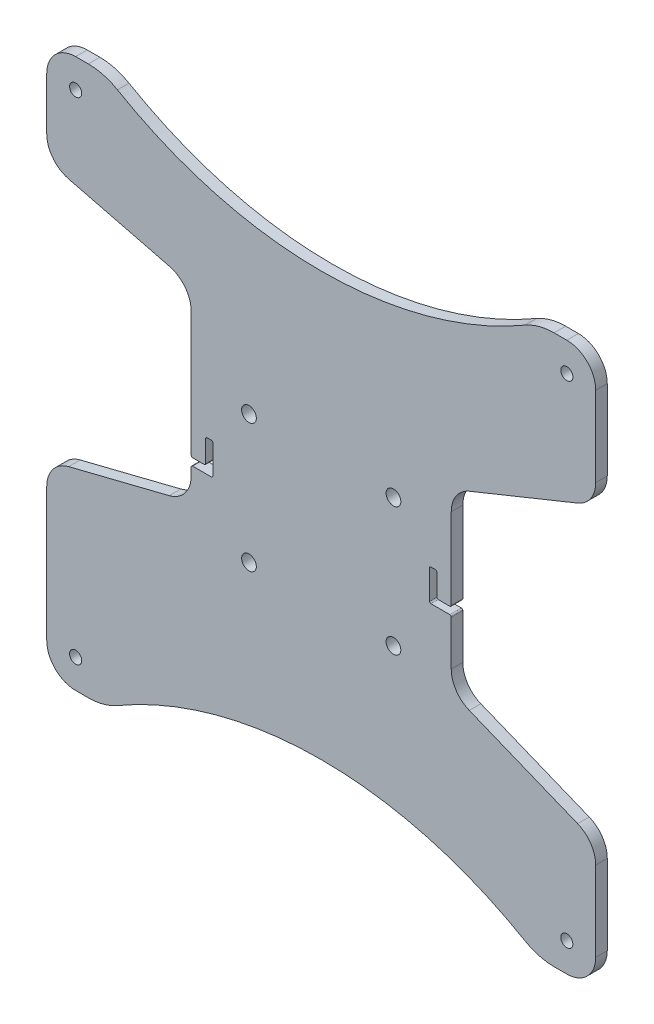
SolidWorks part; units mm, degrees
ref_plane "Front Plane" through (0, 0, 0) normal (0, 0, 1) x (1, 0, 0)
ref_plane "Top Plane" through (0, 0, 0) normal (0, 1, 0) x (1, 0, 0)
ref_plane "Right Plane" through (0, 0, 0) normal (1, 0, 0) x (0, 0, -1)
ref_plane "Plane1" through (0, 0, 0) normal (0, 0, -1) x (-1, 0, 0)
sketch "Sketch1" plane through (0, 0, 0) normal (0, 0, -1) x (-1, 0, 0)
  line L0 (87.4254, -29.1063) -> (52.5746, -20.3937)
  line L1 (45, -10.6922) -> (45, -8)
  line L2 (44.5, -7.5) -> (38, -7.5)
  line L3 (37.5, -7) -> (37.5, 3)
  line L4 (38, 3.5) -> (39.5, 3.5)
  line L5 (40, 3) -> (40, -4.5)
  line L6 (40.5, -5) -> (44.5, -5)
  line L7 (45, -4.5) -> (45, 38.6922)
  line L8 (52.5746, 48.3937) -> (87.4254, 57.1063)
  line L9 (95, 66.8078) -> (95, 85)
  line L10 (85, 95) -> (80.6, 95)
  line L11 (-80.6, 95) -> (-85, 95)
  line L12 (-95, 85) -> (-95, 57.3099)
  line L13 (-88.7544, 48.0415) -> (-51.2456, 32.8477)
  line L14 (-45, 23.5792) -> (-45, -4.5)
  line L15 (-44.5, -5) -> (-40.5, -5)
  line L16 (-40, -4.5) -> (-40, 3)
  line L17 (-39.5, 3.5) -> (-38, 3.5)
  line L18 (-37.5, 3) -> (-37.5, -7)
  line L19 (-38, -7.5) -> (-44.5, -7.5)
  line L20 (-45, -8) -> (-45, -23.5792)
  line L21 (-51.2456, -32.8477) -> (-88.7544, -48.0415)
  line L22 (-95, -57.3099) -> (-95, -85)
  line L23 (-85, -95) -> (-80.6, -95)
  line L24 (80.6, -95) -> (85, -95)
  line L25 (95, -85) -> (95, -38.8078)
  circle A0 centre (-85, -85) radius 2.1
  circle A1 centre (-85, 85) radius 2.1
  circle A2 centre (85, 85) radius 2.1
  circle A3 centre (85, -85) radius 2.1
  circle A4 centre (25, 17.8732) radius 2.55
  circle A5 centre (25, -26.6068) radius 2.54
  circle A6 centre (-25, -26.6068) radius 2.54
  circle A7 centre (-25, 17.8732) radius 2.55
  arc A8 (52.5746, -20.3937) -> (45, -10.6922) centre (55, -10.6922) cw
  arc A9 (45, -8) -> (44.5, -7.5) centre (44.5, -8) ccw
  arc A10 (38, -7.5) -> (37.5, -7) centre (38, -7) cw
  arc A11 (37.5, 3) -> (38, 3.5) centre (38, 3) cw
  arc A12 (39.5, 3.5) -> (40, 3) centre (39.5, 3) cw
  arc A13 (40, -4.5) -> (40.5, -5) centre (40.5, -4.5) ccw
  arc A14 (44.5, -5) -> (45, -4.5) centre (44.5, -4.5) ccw
  arc A15 (45, 38.6922) -> (52.5746, 48.3937) centre (55, 38.6922) cw
  arc A16 (87.4254, 57.1063) -> (95, 66.8078) centre (85, 66.8078) ccw
  arc A17 (95, 85) -> (85, 95) centre (85, 85) ccw
  arc A18 (80.6, 95) -> (70.525, 92.277) centre (80.6, 75) ccw
  arc A19 (70.525, 92.277) -> (-70.525, 92.277) centre (0, 213.2159) cw
  arc A20 (-70.525, 92.277) -> (-80.6, 95) centre (-80.6, 75) ccw
  arc A21 (-85, 95) -> (-95, 85) centre (-85, 85) ccw
  arc A22 (-95, 57.3099) -> (-88.7544, 48.0415) centre (-85, 57.3099) ccw
  arc A23 (-51.2456, 32.8477) -> (-45, 23.5792) centre (-55, 23.5792) cw
  arc A24 (-45, -4.5) -> (-44.5, -5) centre (-44.5, -4.5) ccw
  arc A25 (-40.5, -5) -> (-40, -4.5) centre (-40.5, -4.5) ccw
  arc A26 (-40, 3) -> (-39.5, 3.5) centre (-39.5, 3) cw
  arc A27 (-38, 3.5) -> (-37.5, 3) centre (-38, 3) cw
  arc A28 (-37.5, -7) -> (-38, -7.5) centre (-38, -7) cw
  arc A29 (-44.5, -7.5) -> (-45, -8) centre (-44.5, -8) ccw
  arc A30 (-45, -23.5792) -> (-51.2456, -32.8477) centre (-55, -23.5792) cw
  arc A31 (-88.7544, -48.0415) -> (-95, -57.3099) centre (-85, -57.3099) ccw
  arc A32 (-95, -85) -> (-85, -95) centre (-85, -85) ccw
  arc A33 (-80.6, -95) -> (-70.525, -92.277) centre (-80.6, -75) ccw
  arc A34 (-70.525, -92.277) -> (70.525, -92.277) centre (0, -213.2159) cw
  arc A35 (70.525, -92.277) -> (80.6, -95) centre (80.6, -75) ccw
  arc A36 (85, -95) -> (95, -85) centre (85, -85) ccw
  arc A37 (95, -38.8078) -> (87.4254, -29.1063) centre (85, -38.8078) ccw
  point P98 (26.5116, 20.1)
  point P99 (-13.2845, 20.1)
  point P100 (26.5116, -26.6068)
  point P101 (-13.2845, -26.6068)
  dimension "D1" = 44.48
  dimension "D2" = 44.48
  dimension "D3" = 20
  dimension "D4" = 20
extrude "Boss-Extrude1" add sketch "Sketch1" against normal blind 4
